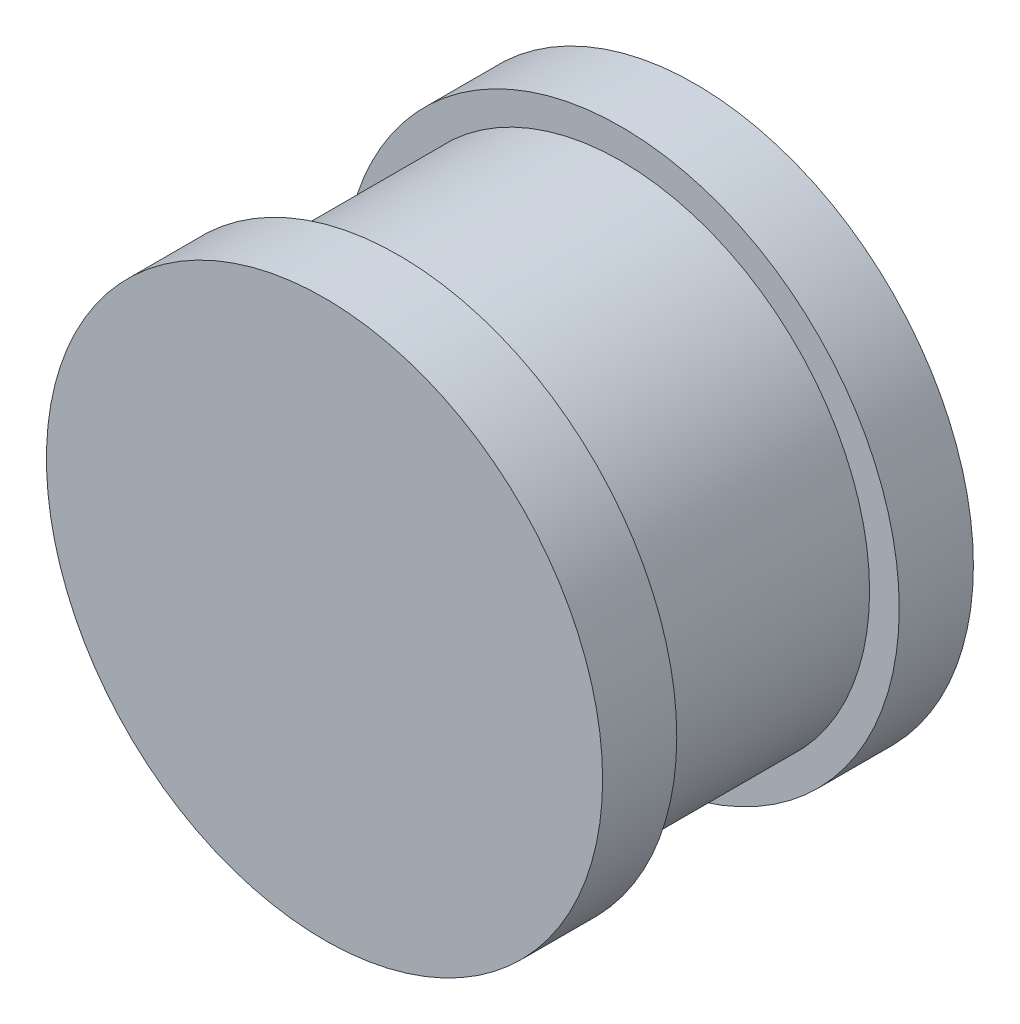
SolidWorks part; units mm, degrees
ref_plane "Front Plane" through (0, 0, 0) normal (0, 0, 1) x (1, 0, 0)
ref_plane "Top Plane" through (0, 0, 0) normal (0, 1, 0) x (1, 0, 0)
ref_plane "Right Plane" through (0, 0, 0) normal (1, 0, 0) x (0, 0, -1)
sketch "Sketch1" plane through (0, 0, 0) normal (0, 1, 0) x (1, 0, 0)
  line L0 (0, 0) -> (3.75, 0)
  line L1 (3.75, 0) -> (3.75, -1)
  line L2 (3.75, -1) -> (3.35, -1)
  line L3 (3.35, -1) -> (3.35, -4)
  line L4 (3.35, -4) -> (3.75, -4)
  line L5 (3.75, -4) -> (3.75, -5)
  line L6 (3.75, -5) -> (0, -5)
  line L7 (0, -5) -> (0, 0)
  point P3 (0, 0)
  dimension "D1" = 5
  dimension "D2" = 3.75
  dimension "D3" = 1
  dimension "D4" = 0.4
revolve "Revolve1" add sketch "Sketch1" angle 360 about L7
